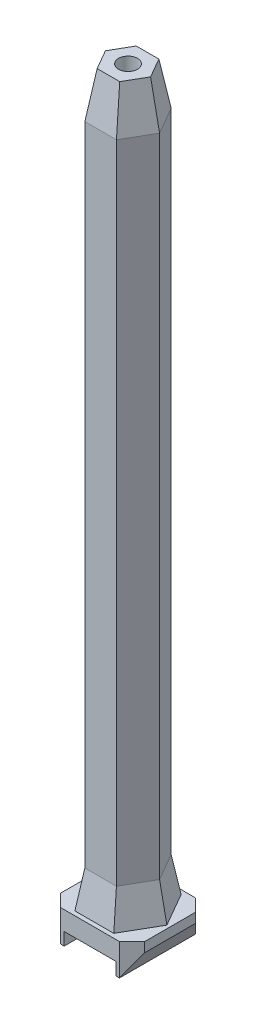
SolidWorks part; units mm, degrees
ref_plane "Front Plane" through (0, 0, 0) normal (0, 0, 1) x (1, 0, 0)
ref_plane "Top Plane" through (0, 0, 0) normal (0, 1, 0) x (1, 0, 0)
ref_plane "Right Plane" through (0, 0, 0) normal (1, 0, 0) x (0, 0, -1)
sketch "Sketch1" plane through (0, 0, 0) normal (0, 1, 0) x (1, 0, 0)
  line L1 (-6.6465, -6) -> (6.6465, -6)
  line L2 (-6.6465, -6) -> (-6.6465, 6)
  line L3 (-6.6465, 6) -> (6.6465, 6)
  line L4 (6.6465, -6) -> (6.6465, 6)
  line L5 (-6.6465, -6) -> (6.6465, 6) construction
  line L6 (-6.6465, 6) -> (6.6465, -6) construction
  point P0 (0, 0)
  dimension "D1" = 12
extrude "Boss-Extrude1" add sketch "Sketch1" along normal blind 120
sketch "Sketch2" plane through (0, 0, 0) normal (0, -1, 0) x (1, 0, 0)
  line L1 (-4.1, -27.014) -> (4.1, -27.014)
  line L2 (-4.1, -27.014) -> (-4.1, 27.014)
  line L3 (-4.1, 27.014) -> (4.1, 27.014)
  line L4 (4.1, -27.014) -> (4.1, 27.014)
  line L5 (-4.1, -27.014) -> (4.1, 27.014) construction
  line L6 (-4.1, 27.014) -> (4.1, -27.014) construction
  point P0 (0, 0)
  dimension "D1" = 8.2
extrude "Cut-Extrude1" cut sketch "Sketch2" against normal blind 2
sketch "Sketch3" plane through (0, 120, 0) normal (0, 1, 0) x (1, 0, 0)
  circle A0 centre (0, 0) radius 1.5
  dimension "D1" = 3
extrude "Cut-Extrude2" cut sketch "Sketch3" against normal blind 140
sketch "Sketch4" plane through (0, 120, 0) normal (0, 1, 0) x (1, 0, 0)
  line L0 (-2.5, -4.3301) -> (2.5, -4.3301)
  line L1 (2.5, 4.3301) -> (-2.5, 4.3301)
  line L2 (-2.5, 4.3301) -> (-5, 0)
  line L3 (-5, 0) -> (-2.5, -4.3301)
  line L4 (2.5, -4.3301) -> (5, 0)
  line L5 (5, 0) -> (2.5, 4.3301)
  circle A0 centre (0, 0) radius 4.3301 construction
  point P9 (2.6829, 4.6469)
  dimension "D1" = 5
extrude "Cut-Extrude3" cut sketch "Sketch4" against normal blind 115 flip side to cut
chamfer "Chamfer1" distance 1 angle 80 6 edges at (-3.75, 5, -2.1651) (0, 5, -4.3301) (3.75, 5, -2.1651) (3.75, 5, 2.1651) (0, 5, 4.3301) (-3.75, 5, 2.1651)
chamfer "Chamfer2" distance 2 angle 45 4 edges at (6.6465, 2.5, -6) (-6.6465, 2.5, -6) (6.6465, 2.5, 6) (-6.6465, 2.5, 6)
chamfer "Chamfer3" distance 7 angle 10 6 edges at (0, 120, 4.3301) (-3.75, 120, 2.1651) (-3.75, 120, -2.1651) (0, 120, -4.3301) (3.75, 120, -2.1651) (3.75, 120, 2.1651)
chamfer "Chamfer4" distance 2 angle 60 2 edges at (-6.6465, 0, 0) (6.6465, 0, 0)
